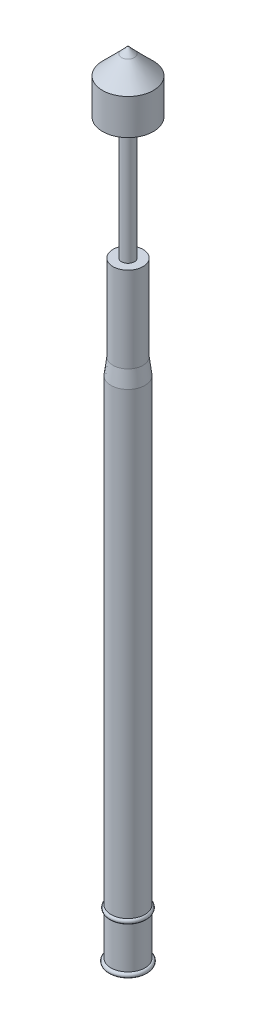
SolidWorks part; units mm, degrees
ref_plane "前视基准面" through (0, 0, 0) normal (0, 0, 1) x (1, 0, 0)
ref_plane "上视基准面" through (0, 0, 0) normal (0, 1, 0) x (1, 0, 0)
ref_plane "右视基准面" through (0, 0, 0) normal (1, 0, 0) x (0, 0, -1)
other "Configuration Table"
sketch "草图1" plane through (0, 0, 0) normal (0, 1, 0) x (1, 0, 0)
  circle A0 centre (0, 0) radius 0.835
  dimension "D1" = 1.67
extrude "凸台-拉伸1" add sketch "草图1" along normal blind 25
sketch "草图2" plane through (0, 25, 0) normal (0, 1, 0) x (1, 0, 0)
  circle A0 centre (0, 0) radius 0.735
  dimension "D1" = 1.47
extrude "凸台-拉伸2" add sketch "草图2" along normal blind 5
sketch "草图3" plane through (0, 30, 0) normal (0, 1, 0) x (1, 0, 0)
  circle A0 centre (0, 0) radius 0.32
  dimension "D1" = 0.64
extrude "凸台-拉伸3" add sketch "草图3" along normal blind 9
sketch "草图5" plane through (0, 0, 0) normal (0, 0, 1) x (1, 0, 0)
  line L0 (0.835, 25) -> (0.735, 25.8)
  line L1 (0.735, 25) -> (0.735, 30) construction
  line L2 (0.735, 25.8) -> (0.735, 25)
  line L3 (0.735, 25) -> (0.835, 25)
  line L4 (0, 0) -> (0, 0.7809) construction
  line L7 (0, 0.115) -> (0.95, 0.115) construction
  line L8 (0.835, 0) -> (0.835, 25) construction
  line L9 (0.835, 0.23) -> (0.835, 0)
  line L10 (-0.835, 0) -> (0.835, 0) construction
  line L11 (0, 2.385) -> (0.915, 2.385) construction
  line L12 (0.835, 2.5) -> (0.835, 2.27)
  arc A0 (0.835, 0.23) -> (0.835, 0) centre (0.835, 0.115) cw
  arc A1 (0.835, 2.5) -> (0.835, 2.27) centre (0.7923, 2.385) cw
  dimension "D1" = 0.8
  dimension "D2" = 0.95
  dimension "D3" = 0.915
  dimension "D4" = 2.5
revolve "旋转1" add sketch "草图5" angle 360 about L4
sketch "草图6" plane through (0, 0, 0) normal (0, 0, 1) x (1, 0, 0)
  line L0 (0, 0) -> (0, -1.2565) construction
  line L2 (0, 39) -> (-1.25, 37.75)
  line L3 (0.32, 39) -> (-0.32, 39) construction
  line L4 (-1.25, 37.75) -> (-1.25, 36)
  line L5 (-1.25, 36) -> (0, 36)
  line L6 (0, 36) -> (0, 39)
  point P7 (-1, 38)
  dimension "D1" = 1.25
  dimension "D2" = 3
  dimension "D3" = 135
revolve "旋转2" add sketch "草图6" angle 360 about L0
sketch "草图7" plane through (0, 0, 0) normal (0, 0, 1) x (1, 0, 0)
  line L0 (0, 0) -> (0, -1.5384) construction
  line L7 (0.32, 39) -> (0.02, 39)
  line L8 (0.32, 39) -> (-0.32, 39) construction
  line L9 (0.02, 39) -> (0.32, 38.68)
  line L10 (0.32, 38.68) -> (-0.32, 38.68) construction
  line L11 (0.32, 38.68) -> (0.32, 39) construction
  line L12 (0.32, 38.68) -> (0.32, 39)
  dimension "D1" = 0.3
revolve "切除-旋转5" cut sketch "草图7" angle 360 about L0
